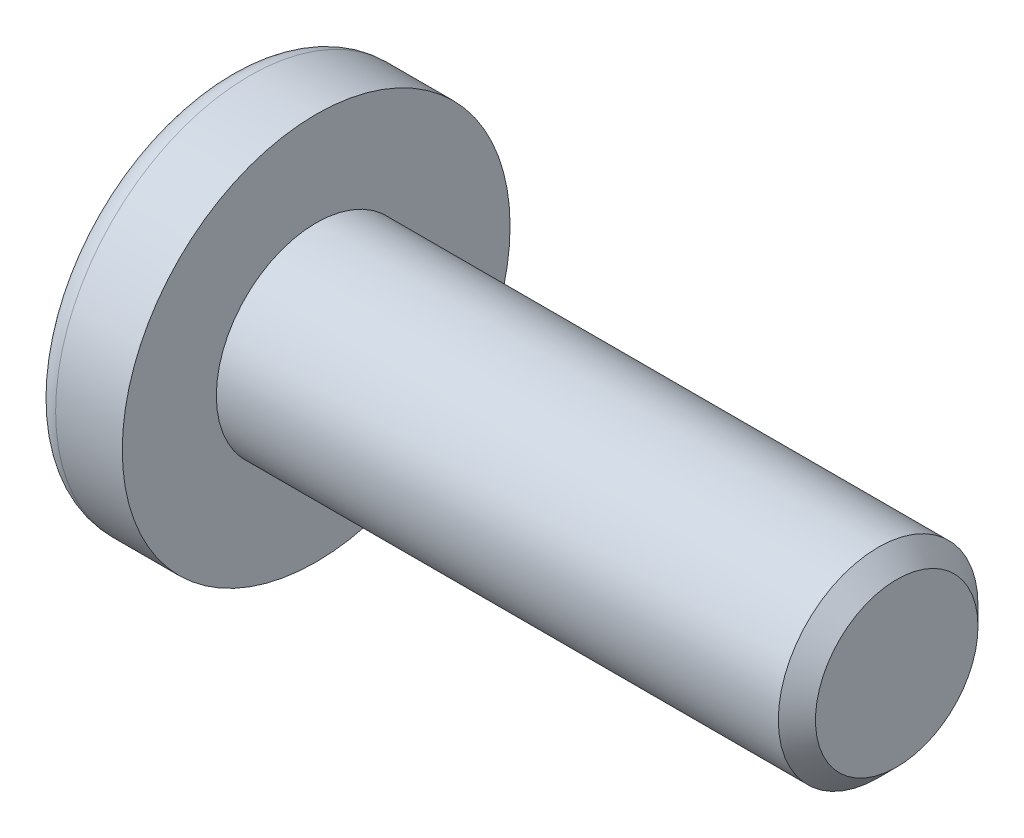
SolidWorks part; units mm, degrees
material "Alloy Steel"
ref_plane "Plane1" through (0, 0, 0) normal (0, 0, 1) x (1, 0, 0)
ref_plane "Plane2" through (0, 0, 0) normal (0, 1, 0) x (1, 0, 0)
ref_plane "Plane3" through (0, 0, 0) normal (1, 0, 0) x (0, 0, -1)
sketch "BodySke" plane through (0, 0, 0) normal (0, 0, 1) x (1, 0, 0)
  line L0 (1.5748, 1.0922) -> (1.5748, 2.1209)
  line L1 (1.8021, 6.35) -> (1.8021, -3.175) construction
  line L2 (-25.4, 0) -> (127, 0) construction
  line L3 (7.9248, 0) -> (0, 0)
  line L4 (1.5748, 1.0922) -> (7.9248, 1.0922)
  line L5 (7.9248, 1.0922) -> (7.9248, 0)
  line L6 (0.8457, 2.1209) -> (1.5748, 2.1209)
  line L7 (1.5748, -1.0922) -> (7.9248, -1.0922) construction
  line L8 (1.5748, 6.35) -> (1.5748, -3.175) construction
  arc A0 (0.6381, 2.0132) -> (0, 0) centre (3.495, 0) ccw
  arc A2 (0.6381, 2.0132) -> (0.8457, 2.1209) centre (0.8457, 1.8669) cw
  dimension "Head_fillet_rad" = 0.254
  dimension "Head_crown_rad" = 3.495
  dimension "Head_ht" = 1.5748
  dimension "Diameter" = 2.1844
  dimension "Length" = 6.35
  dimension "Head_dia" = 4.2418
  dimension "Advance" = 0.4547
  dimension "Thread_nom" = 6.35
revolve "Base-Revolve" add sketch "BodySke" angle 360 about L2
cosmetic thread "ThreadCosmetic" parameters "Thread_length"=5.8953, "Thread_minor"=1.6459
sketch "Sketch3" plane through (0, 0, 0) normal (1, 0, 0) x (0, 0, -1)
  line L0 (0.3429, -1.3843) -> (-0.3429, -1.3843)
  line L1 (0.3429, -1.3843) -> (0.3429, 1.3843)
  line L2 (-0.3429, 1.3843) -> (0.3429, 1.3843)
  line L3 (-0.3429, 1.3843) -> (-0.3429, -1.3843)
  dimension "D1" = 1.3843
  dimension "Cross_dia" = 2.7686
  dimension "D2" = 0.3429
  dimension "Cross_width" = 0.6858
ref_plane "Plane4" through (1.4986, 0, 0) normal (1, 0, 0) x (0, 0, -1)
sketch "Sketch4" plane through (1.4986, 0, 0) normal (1, 0, 0) x (0, 0, -1)
  line L0 (0.1714, -0.1715) -> (-0.1714, -0.1715)
  line L1 (0.1714, -0.1715) -> (0.1714, 0.1715)
  line L2 (-0.1714, 0.1714) -> (0.1714, 0.1715)
  line L3 (-0.1714, 0.1714) -> (-0.1714, -0.1715)
  dimension "D1" = 0.3429
  dimension "D2" = 0.3429
  dimension "D3" = 0.1714
  dimension "D4" = 0.1714
loft "Cut-Loft1" cut profiles "Sketch3", "Sketch4"
pattern_circular "CirPattern1" count 2 every 90 about axis through (0, 0, 0) along (1, 0, 0) of "Cut-Loft1"
chamfer "Chamfer1" distance 0.2032 angle 45 1 edges at (7.9248, 0, 1.0922)
equation "\"D1@Sketch3\" = \"Cross_dia@Sketch3\" / 2"
equation "\"D2@Sketch3\" = \"Cross_width@Sketch3\" / 2"
equation "\"D1@Sketch4\" = \"Cross_width@Sketch3\" *.5"
equation "\"D2@Sketch4\" = \"D1@Sketch4\""
equation "\"D3@Sketch4\" = \"D1@Sketch4\" / 2"
equation "\"D4@Sketch4\" = \"D2@Sketch4\" / 2"
equation "\"Thread_length@ThreadCosmetic\" = ((sgn( (\"Length@BodySke\" - \"Advance@BodySke\" ) - \"Thread_nom@BodySke\" )-1)*( (\"Length@BodySke\" - \"Advance@BodySke\" ) - \"Thread_nom@BodySke\" ))/-2+ \"Thread_nom@BodySke\""
